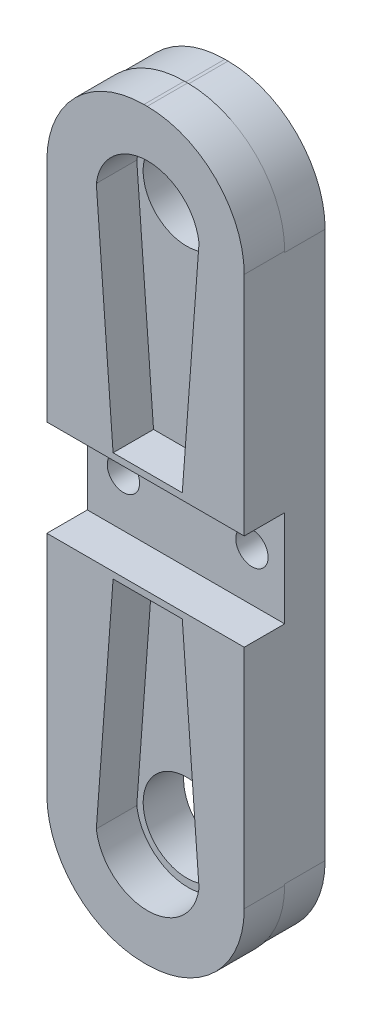
SolidWorks part; units mm, degrees
ref_plane "Front Plane" through (0, 0, 0) normal (0, 0, 1) x (1, 0, 0)
ref_plane "Top Plane" through (0, 0, 0) normal (0, 1, 0) x (1, 0, 0)
ref_plane "Right Plane" through (0, 0, 0) normal (1, 0, 0) x (0, 0, -1)
other "Graphic1"
ref_plane "Plane1" through (0, 0, 10) normal (0, 0, 1) x (1, 0, 0)
sketch "Sketch1" plane through (0, 0, 10) normal (0, 0, 1) x (1, 0, 0)
  line L1 (-188.2312, 182.8882) -> (-176.0312, 182.8882)
  line L2 (-188.2312, 182.8882) -> (-188.2312, 137.0882)
  line L3 (-188.2312, 137.0882) -> (-176.0312, 137.0882)
  line L4 (-176.0312, 182.8882) -> (-176.0312, 137.0882)
  dimension "D1" = 12.2
  dimension "D2" = 45.8
extrude "Boss-Extrude1" add sketch "Sketch1" along normal blind 2.5
fillet "Fillet1" radius 6 4 edges at (-176.0312, 182.8882, 11.25) (-188.2312, 182.8882, 11.25) (-176.0312, 137.0882, 11.25) (-188.2312, 137.0882, 11.25)
sketch "Sketch2" plane through (0, 0, 12.5) normal (0, 0, 1) x (1, 0, 0)
  line L0 (-188.2312, 159.9882) -> (-146.0551, 159.9882) construction
  line L2 (-176.0312, 143.0882) -> (-176.0312, 176.8882) construction
  line L3 (-176.0312, 162.9655) -> (-188.2312, 162.9655)
  line L4 (-176.0312, 162.9655) -> (-176.0312, 182.9655)
  line L5 (-176.0312, 182.9655) -> (-188.2312, 182.9655)
  line L6 (-188.2312, 162.9655) -> (-188.2312, 182.9655)
  line L7 (-188.2312, 176.8882) -> (-188.2312, 143.0882) construction
  line L8 (-176.0312, 137.0109) -> (-188.2312, 137.0109)
  line L9 (-188.2312, 157.0109) -> (-188.2312, 137.0109)
  line L10 (-176.0312, 157.0109) -> (-188.2312, 157.0109)
  line L11 (-176.0312, 157.0109) -> (-176.0312, 137.0109)
  dimension "D1" = 20
  dimension "D2" = 12.2
extrude "Boss-Extrude2" add sketch "Sketch2" along normal blind 2.5
fillet "Fillet2" radius 6 4 edges at (-188.2312, 182.9655, 13.75) (-176.0312, 182.9655, 13.75) (-188.2312, 137.0109, 13.75) (-176.0312, 137.0109, 13.75)
sketch "Sketch3" plane through (0, 0, 12.5) normal (0, 0, 1) x (1, 0, 0)
  circle A0 centre (-185.9997, 160.0579) radius 1
  circle A1 centre (-178.0549, 160.0579) radius 1
extrude "Cut-Extrude1" cut sketch "Sketch3" against normal blind 2.5
sketch "Sketch4" plane through (0, 0, 15) normal (0, 0, 1) x (1, 0, 0)
  line L0 (-184.1384, 163.3657) -> (-179.8616, 163.3657)
  line L1 (-179.8616, 163.3657) -> (-178.8249, 177.2648)
  line L2 (-184.1384, 163.3657) -> (-185.1751, 177.2648)
  line L3 (-176.0312, 159.9882) -> (-170.1506, 159.9882) construction
  line L4 (-176.0312, 157.0109) -> (-176.0312, 162.9655) construction
  line L5 (-184.1384, 156.6106) -> (-185.1751, 142.7116)
  line L6 (-184.1384, 156.6106) -> (-179.8616, 156.6106)
  line L7 (-179.8616, 156.6106) -> (-178.8249, 142.7116)
  arc A0 (-185.1751, 177.2648) -> (-178.8249, 177.2648) centre (-182, 176.8585) cw
  arc A1 (-185.1751, 142.7116) -> (-178.8249, 142.7116) centre (-182, 143.1178) ccw
extrude "Cut-Extrude2" cut sketch "Sketch4" against normal up to vertex (2.5 mm away) up to point (-188.2312, 162.9655, 12.5)
sketch "Sketch5" plane through (0, 0, 12.5) normal (0, 0, 1) x (1, 0, 0)
  line L0 (-176.0312, 159.9882) -> (-170.9247, 159.9882) construction
  line L1 (-176.0312, 157.0109) -> (-176.0312, 162.9655) construction
  circle A0 centre (-182.0806, 176.9002) radius 2.7
  circle A1 centre (-182.0806, 143.0762) radius 2.7
extrude "Cut-Extrude3" cut sketch "Sketch5" against normal blind 2.5
